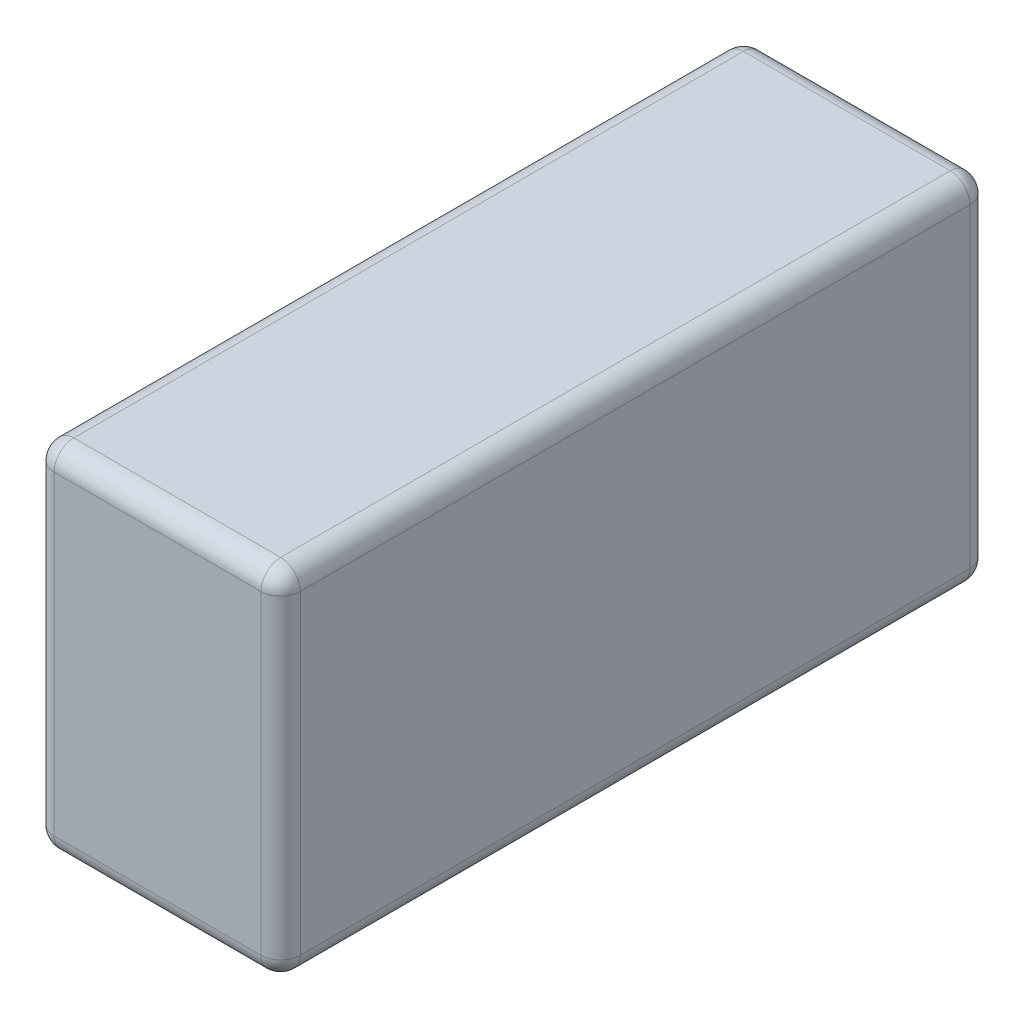
SolidWorks part; units mm, degrees
ref_plane "Alzado" through (0, 0, 0) normal (0, 0, 1) x (1, 0, 0)
ref_plane "Planta" through (0, 0, 0) normal (0, 1, 0) x (1, 0, 0)
ref_plane "Vista lateral" through (0, 0, 0) normal (1, 0, 0) x (0, 0, -1)
sketch "Croquis1" plane through (0, 0, 0) normal (0, 0, 1) x (1, 0, 0)
  line L1 (-12.5, 18) -> (12.5, 18)
  line L2 (-12.5, 18) -> (-12.5, -18)
  line L3 (-12.5, -18) -> (12.5, -18)
  line L4 (12.5, 18) -> (12.5, -18)
  line L5 (-12.5, 18) -> (12.5, -18) construction
  line L6 (-12.5, -18) -> (12.5, 18) construction
  point P0 (0, 0)
  dimension "D1" = 36
  dimension "D2" = 25
extrude "Saliente-Extruir1" add sketch "Croquis1" along normal blind 72
fillet "Redondeo1" radius 2 12 edges at (0, -18, 72) (-12.5, 0, 72) (0, 18, 72) (12.5, 0, 72) (-12.5, -18, 36) (-12.5, 18, 36) (-12.5, 0, 0) (0, -18, 0) (12.5, -18, 36) (12.5, 0, 0) (12.5, 18, 36) (0, 18, 0)
